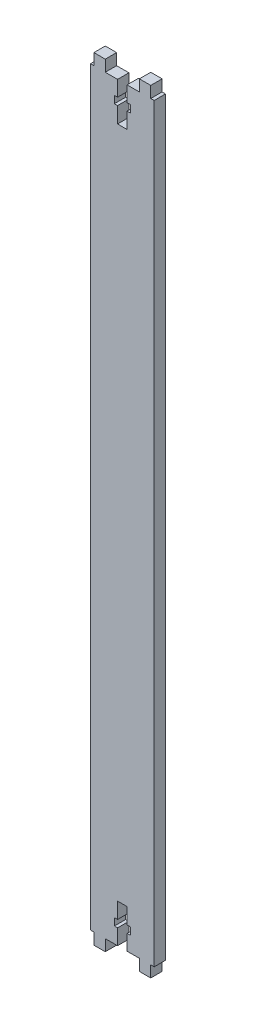
SolidWorks part; units mm, degrees
ref_plane "Front Plane" through (0, 0, 0) normal (0, 0, 1) x (1, 0, 0)
ref_plane "Top Plane" through (0, 0, 0) normal (0, 1, 0) x (1, 0, 0)
ref_plane "Right Plane" through (0, 0, 0) normal (1, 0, 0) x (0, 0, -1)
sketch "Sketch1" plane through (0, 0, 0) normal (0, 0, 1) x (1, 0, 0)
  line L0 (-14, 330) -> (-14, 326.9742) construction
  line L1 (-28, 330) -> (0, 330)
  line L2 (-28, 330) -> (-28, 0)
  line L3 (-28, 0) -> (0, 0)
  line L4 (0, 330) -> (0, 0)
  line L6 (-26.5, 330) -> (-26.5, 335)
  line L7 (-26.5, 335) -> (-21.5, 335)
  line L8 (-21.5, 330) -> (-21.5, 335)
  line L10 (-16.1, 330) -> (-16.1, 313)
  line L11 (-16.1, 313) -> (-11.9, 313)
  line L12 (-11.9, 330) -> (-11.9, 313)
  line L13 (-17.5, 323.2) -> (-10.5, 323.2)
  line L14 (-17.5, 323.2) -> (-17.5, 320)
  line L15 (-17.5, 320) -> (-10.5, 320)
  line L16 (-10.5, 323.2) -> (-10.5, 320)
  line L17 (-1.5, 335) -> (-6.5, 335)
  line L18 (-6.5, 330) -> (-6.5, 335)
  line L20 (-1.5, 330) -> (-1.5, 335)
  line L21 (-28, 165) -> (27.9161, 165) construction
  line L22 (-14, 0) -> (-14, 3.0258) construction
  line L23 (-1.5, 0) -> (-1.5, -5)
  line L25 (-6.5, 0) -> (-6.5, -5)
  line L26 (-1.5, -5) -> (-6.5, -5)
  line L27 (-10.5, 6.8) -> (-10.5, 10)
  line L28 (-17.5, 10) -> (-10.5, 10)
  line L29 (-17.5, 6.8) -> (-17.5, 10)
  line L30 (-17.5, 6.8) -> (-10.5, 6.8)
  line L31 (-11.9, 0) -> (-11.9, 17)
  line L32 (-16.1, 17) -> (-11.9, 17)
  line L33 (-16.1, 0) -> (-16.1, 17)
  line L35 (-21.5, 0) -> (-21.5, -5)
  line L36 (-26.5, -5) -> (-21.5, -5)
  line L37 (-26.5, 0) -> (-26.5, -5)
  point P9 (-24, 335)
  point P10 (-14, 330)
  point P19 (-14, 313)
  point P20 (-14, 320)
  dimension "D1" = 28
  dimension "D2" = 330
  dimension "D3" = 5
  dimension "D4" = 10
  dimension "D5" = 6.8
  dimension "D6" = 3.2
  dimension "D7" = 17
  dimension "D8" = 4.2
  dimension "D9" = 7
  dimension "D10" = 5
extrude "Boss-Extrude1" add sketch "Sketch1" along normal blind 5 contours L1 L20 L17 L18 | L1 L8 L7 L6 | L3 L33 L30 L29 L28 L32 L31 L27 L4 L1 L12 L13 L16 L15 L11 L10 L14 L2 | L26 L23 L3 L25 | L3 L37 L36 L35
